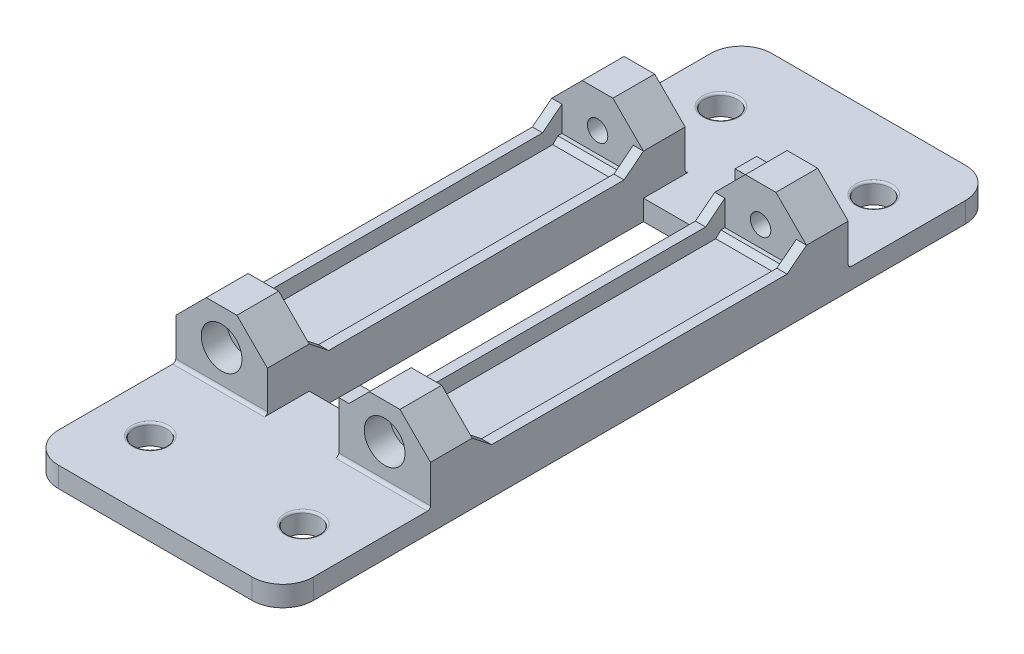
SolidWorks part; units mm, degrees
ref_plane "Front Plane" through (0, 0, 0) normal (0, 0, 1) x (1, 0, 0)
ref_plane "Top Plane" through (0, 0, 0) normal (0, 1, 0) x (1, 0, 0)
ref_plane "Right Plane" through (0, 0, 0) normal (1, 0, 0) x (0, 0, -1)
sketch "Sketch1" plane through (0, 0, 0) normal (0, 1, 0) x (1, 0, 0)
  line L0 (-12.5, -19) -> (-12.5, -12.75)
  line L1 (-12.5, 19) -> (12.5, 19)
  line L2 (-12.5, 19) -> (-12.5, 12.75)
  line L3 (-12.5, -19) -> (12.5, -19)
  line L4 (12.5, 19) -> (12.5, -19)
  line L5 (-14.5, 10.75) -> (-19, 10.75)
  line L7 (-14.5, -10.75) -> (-19, -10.75)
  line L8 (-24, 5.75) -> (-24, -5.75)
  line L9 (-22.342, 7.842) -> (-6.7508, -7.7492) construction
  line L10 (-3, 5) -> (3, 5)
  line L11 (-20.7704, -6.2704) -> (-8.3892, 6.1108) construction
  line L12 (-3, 5) -> (-3, -5)
  line L13 (-3, -5) -> (3, -5)
  line L14 (3, 5) -> (3, -5)
  arc A0 (-24, 5.75) -> (-19, 10.75) centre (-19, 5.75) cw
  arc A1 (-19, -10.75) -> (-24, -5.75) centre (-19, -5.75) cw
  arc A2 (-12.5, 12.75) -> (-14.5, 10.75) centre (-14.5, 12.75) cw
  arc A3 (-12.5, -12.75) -> (-14.5, -10.75) centre (-14.5, -12.75) ccw
  circle A4 centre (-14.5, 0) radius 1.5
  circle A5 centre (0, 8) radius 1
  circle A6 centre (8, 0) radius 1
  circle A7 centre (0, -8) radius 1
  circle A8 centre (-8, 0) radius 1
  circle A9 centre (-20.1569, 5.6569) radius 1
  circle A10 centre (-20.1569, -5.6569) radius 1
  circle A11 centre (-8.8431, -5.6569) radius 1
  circle A12 centre (-8.8431, 5.6569) radius 1
  circle A13 centre (8, 8) radius 1
  circle A14 centre (8, -8) radius 1
  dimension "D8" = 5
  dimension "D9" = 2
  dimension "D10" = 2
  dimension "D11" = 14.5
  dimension "D12" = 8
  dimension "D16" = 8
  dimension "D17" = 8
  dimension "D20" = 8
  dimension "D24" = 3
  dimension "D25" = 3
  dimension "D1" = 12.5
  dimension "D2" = 12.5
  dimension "D3" = 19
  dimension "D4" = 19
  dimension "D5" = 10.75
  dimension "D6" = 10.75
  dimension "D7" = 11.5
  dimension "D13" = 8
  dimension "D14" = 8
  dimension "D15" = 8
  dimension "D18" = 8
  dimension "D19" = 8
  dimension "D21" = 8
  dimension "D22" = 8
  dimension "D23" = 8
  dimension "D26" = 5
  dimension "D27" = 5
extrude "Extrude1" add sketch "Sketch1" along normal blind 3
sketch "Sketch2" plane through (0, 0, 0) normal (0, 1, 0) x (1, 0, 0)
  line L0 (-19.5597, -3.4261) -> (-17.9263, -5.0587)
  line L1 (-19.2603, -2.3108) -> (-16.8108, -4.7603)
  line L2 (-6.3937, 3.2074) -> (-9.7397, 2.3108)
  line L3 (-5.4971, 6.5534) -> (-6.3937, 3.2074)
  line L4 (-20.1569, 5.6569) -> (-8.8431, -5.6569) construction
  line L5 (-7.9466, 9.0029) -> (-5.4971, 6.5534)
  line L6 (-11.2926, 8.1063) -> (-7.9466, 9.0029)
  line L7 (-11.2926, 8.1063) -> (-12.1892, 4.7603)
  line L8 (-7.2104, 4.0234) -> (-9.4413, 3.4263)
  line L9 (-6.6122, 6.254) -> (-7.2104, 4.0234)
  line L10 (-8.2447, 7.8874) -> (-6.6122, 6.254)
  line L11 (-19.5597, -3.4261) -> (-21.7902, -4.0244)
  line L12 (-21.7902, -4.0244) -> (-22.3874, -6.2553)
  line L13 (-22.3874, -6.2553) -> (-20.754, -7.8878)
  line L14 (-20.754, -7.8878) -> (-18.5234, -7.2896)
  line L15 (-18.5234, -7.2896) -> (-17.9263, -5.0587)
  line L16 (-22.6063, -3.2074) -> (-19.2603, -2.3108)
  line L17 (-22.6063, -3.2074) -> (-23.5029, -6.5534)
  line L18 (-23.5029, -6.5534) -> (-21.0534, -9.0029)
  line L19 (-21.0534, -9.0029) -> (-17.7074, -8.1063)
  line L20 (-17.7074, -8.1063) -> (-16.8108, -4.7603)
  line L21 (-10.4756, 7.2902) -> (-8.2447, 7.8874)
  line L22 (-11.0739, 5.0597) -> (-10.4756, 7.2902)
  line L23 (-12.1892, 4.7603) -> (-9.7397, 2.3108)
  line L24 (-11.0739, 5.0597) -> (-9.4413, 3.4263)
  line L25 (-14.5, 13.9789) -> (-14.5, -13.8529) construction
  line L26 (-17.9261, 5.0597) -> (-19.5587, 3.4263)
  line L27 (-16.8108, 4.7603) -> (-19.2603, 2.3108)
  line L28 (-17.9261, 5.0597) -> (-18.5244, 7.2902)
  line L29 (-18.5244, 7.2902) -> (-20.7553, 7.8874)
  line L30 (-20.7553, 7.8874) -> (-22.3878, 6.254)
  line L31 (-22.3878, 6.254) -> (-21.7896, 4.0234)
  line L32 (-21.7896, 4.0234) -> (-19.5587, 3.4263)
  line L33 (-17.7074, 8.1063) -> (-16.8108, 4.7603)
  line L34 (-17.7074, 8.1063) -> (-21.0534, 9.0029)
  line L35 (-21.0534, 9.0029) -> (-23.5029, 6.5534)
  line L36 (-23.5029, 6.5534) -> (-22.6063, 3.2074)
  line L37 (-22.6063, 3.2074) -> (-19.2603, 2.3108)
  line L38 (-5.4971, 0) -> (-25.9289, 0) construction
  line L39 (-11.0739, -5.0597) -> (-9.4413, -3.4263)
  line L40 (-12.1892, -4.7603) -> (-9.7397, -2.3108)
  line L41 (-11.0739, -5.0597) -> (-10.4756, -7.2902)
  line L42 (-10.4756, -7.2902) -> (-8.2447, -7.8874)
  line L43 (-8.2447, -7.8874) -> (-6.6122, -6.254)
  line L44 (-6.6122, -6.254) -> (-7.2104, -4.0234)
  line L45 (-7.2104, -4.0234) -> (-9.4413, -3.4263)
  line L46 (-11.2926, -8.1063) -> (-12.1892, -4.7603)
  line L47 (-11.2926, -8.1063) -> (-7.9466, -9.0029)
  line L48 (-7.9466, -9.0029) -> (-5.4971, -6.5534)
  line L49 (-5.4971, -6.5534) -> (-6.3937, -3.2074)
  line L50 (-6.3937, -3.2074) -> (-9.7397, -2.3108)
  point P57 (-14.5, 0)
extrude "Extrude2" add sketch "Sketch2" along normal blind 4
sketch "Sketch5" plane through (0, 0, 0) normal (0, 1, 0) x (1, 0, 0)
  line L0 (-1.1547, 10) -> (1.1547, 10)
  line L1 (-8, 0) -> (8, 0) construction
  line L2 (4, 15.3149) -> (4, -11.4926) construction
  line L3 (-2.3094, -8) -> (-1.1547, -10)
  line L4 (-1.1547, -6) -> (-2.3094, -8)
  line L5 (1.1547, -6) -> (-1.1547, -6)
  line L6 (2.3094, -8) -> (1.1547, -6)
  line L7 (-3.4641, -8) -> (-1.7321, -11)
  line L8 (-1.7321, -5) -> (-3.4641, -8)
  line L9 (1.7321, -5) -> (-1.7321, -5)
  line L10 (3.4641, -8) -> (1.7321, -5)
  line L11 (-1.7321, 11) -> (1.7321, 11)
  line L12 (1.1547, 10) -> (2.3094, 8)
  line L13 (1.7321, -11) -> (3.4641, -8)
  line L14 (1.1547, -10) -> (2.3094, -8)
  line L15 (-1.7321, -11) -> (1.7321, -11)
  line L16 (1.7321, 11) -> (3.4641, 8)
  line L17 (3.4641, 8) -> (1.7321, 5)
  line L18 (1.7321, 5) -> (-1.7321, 5)
  line L19 (-1.7321, 5) -> (-3.4641, 8)
  line L20 (-3.4641, 8) -> (-1.7321, 11)
  line L21 (2.3094, 8) -> (1.1547, 6)
  line L22 (1.1547, 6) -> (-1.1547, 6)
  line L23 (-1.1547, 6) -> (-2.3094, 8)
  line L24 (-2.3094, 8) -> (-1.1547, 10)
  line L25 (-1.1547, -10) -> (1.1547, -10)
  line L26 (9.1547, -10) -> (6.8453, -10)
  line L27 (10.3094, 8) -> (9.1547, 10)
  line L28 (9.1547, 6) -> (10.3094, 8)
  line L29 (6.8453, 6) -> (9.1547, 6)
  line L30 (5.6906, 8) -> (6.8453, 6)
  line L31 (11.4641, 8) -> (9.7321, 11)
  line L32 (9.7321, 5) -> (11.4641, 8)
  line L33 (6.2679, 5) -> (9.7321, 5)
  line L34 (4.5359, 8) -> (6.2679, 5)
  line L35 (6.2679, 11) -> (4.5359, 8)
  line L36 (9.7321, -11) -> (6.2679, -11)
  line L37 (6.8453, -10) -> (5.6906, -8)
  line L38 (6.2679, -11) -> (4.5359, -8)
  line L39 (6.8453, 10) -> (5.6906, 8)
  line L40 (9.7321, 11) -> (6.2679, 11)
  line L41 (4.5359, -8) -> (6.2679, -5)
  line L42 (6.2679, -5) -> (9.7321, -5)
  line L43 (9.7321, -5) -> (11.4641, -8)
  line L44 (11.4641, -8) -> (9.7321, -11)
  line L45 (5.6906, -8) -> (6.8453, -6)
  line L46 (6.8453, -6) -> (9.1547, -6)
  line L47 (9.1547, -6) -> (10.3094, -8)
  line L48 (10.3094, -8) -> (9.1547, -10)
  line L49 (9.1547, 10) -> (6.8453, 10)
  line L50 (-4.9483, 4) -> (13.5301, 4) construction
  line L51 (9.1547, -2) -> (6.8453, -2)
  line L52 (9.7321, -3) -> (6.2679, -3)
  line L53 (6.8453, -2) -> (5.6906, 0)
  line L54 (6.2679, -3) -> (4.5359, 0)
  line L55 (4.5359, 0) -> (6.2679, 3)
  line L56 (6.2679, 3) -> (9.7321, 3)
  line L57 (9.7321, 3) -> (11.4641, 0)
  line L58 (11.4641, 0) -> (9.7321, -3)
  line L59 (5.6906, 0) -> (6.8453, 2)
  line L60 (6.8453, 2) -> (9.1547, 2)
  line L61 (9.1547, 2) -> (10.3094, 0)
  line L62 (10.3094, 0) -> (9.1547, -2)
  line L63 (0, 0) -> (-15.423, -15.423) construction
  line L64 (-10, -1.1547) -> (-10, 1.1547)
  line L65 (-11, -1.7321) -> (-11, 1.7321)
  line L66 (-10, 1.1547) -> (-8, 2.3094)
  line L67 (-11, 1.7321) -> (-8, 3.4641)
  line L68 (-8, 3.4641) -> (-5, 1.7321)
  line L69 (-5, 1.7321) -> (-5, -1.7321)
  line L70 (-5, -1.7321) -> (-8, -3.4641)
  line L71 (-8, -3.4641) -> (-11, -1.7321)
  line L72 (-8, 2.3094) -> (-6, 1.1547)
  line L73 (-6, 1.1547) -> (-6, -1.1547)
  line L74 (-6, -1.1547) -> (-8, -2.3094)
  line L75 (-8, -2.3094) -> (-10, -1.1547)
  circle A1 centre (0, 8) radius 1 construction
  dimension "D1" = 4
  dimension "D2" = 4
extrude "Extrude3" add sketch "Sketch5" along normal blind 4
sketch "Sketch7" plane through (0, 0, 0) normal (0, 1, 0) x (1, 0, 0)
  line L0 (-12.5, -19) -> (12.5, -19) construction
  line L1 (-12.5, 19) -> (-11.5, 19)
  line L2 (-12.5, 19) -> (-12.5, -19)
  line L3 (-12.5, -19) -> (-11.5, -19)
  line L4 (-11.5, 19) -> (-11.5, -19)
  line L5 (12.5, 19) -> (-12.5, 19) construction
  line L6 (-4.5, 19) -> (-3.5, 19)
  line L7 (-4.5, 19) -> (-4.5, -19)
  line L8 (-4.5, -19) -> (-3.5, -19)
  line L9 (-3.5, 19) -> (-3.5, 6)
  line L10 (3.5, -6) -> (3.5, -19)
  line L11 (3.5, 19) -> (4.5, 19)
  line L12 (3.5, 19) -> (3.5, 6)
  line L13 (3.5, -19) -> (4.5, -19)
  line L14 (4.5, 19) -> (4.5, -19)
  line L15 (12.5, 19) -> (11.5, 19)
  line L16 (12.5, 19) -> (12.5, -19)
  line L17 (12.5, -19) -> (11.5, -19)
  line L18 (11.5, 19) -> (11.5, -19)
  line L19 (3.5, 6) -> (-3.5, 6)
  line L20 (3.5, -6) -> (-3.5, -6)
  line L21 (-3, 5) -> (3, 5)
  line L22 (-3, 5) -> (-3, -5)
  line L23 (-3, -5) -> (3, -5)
  line L24 (3, 5) -> (3, -5)
  line L25 (-3.5, -6) -> (-3.5, -19)
  dimension "D1" = 7
  dimension "D2" = 1
  dimension "D3" = 7
  dimension "D4" = 1
  dimension "D5" = 7
extrude "Extrude4" add sketch "Sketch7" along normal blind 4.5
sketch "Sketch8" plane through (0, 0, 0) normal (0, 1, 0) x (1, 0, 0)
  line L0 (-11.5, 7.3324) -> (-11.5, 19) construction
  line L2 (-11.5, -19) -> (-11.5, -7.3324) construction
  line L3 (-11.5, -9.7489) -> (-11.5, -10.25)
  line L4 (-12, 9.2511) -> (-19, 9.2511)
  line L5 (-11.5, 9.7511) -> (-11.5, 10.2511)
  line L6 (-12, -9.2489) -> (-19, -9.2489)
  line L7 (-11.5, -19) -> (-11.5, 19) construction
  line L8 (-12, -10.75) -> (-19, -10.75)
  line L9 (-24, -5.75) -> (-24, 5.7511)
  line L10 (-19, 10.7511) -> (-12, 10.7511)
  line L12 (-22.5, 5.7511) -> (-22.5, -5.7489)
  arc A0 (-11.5, -9.7489) -> (-12, -9.2489) centre (-12, -9.7489) ccw
  arc A1 (-19, 9.2511) -> (-22.5, 5.7511) centre (-19, 5.7511) ccw
  arc A2 (-19, -9.2489) -> (-22.5, -5.7489) centre (-19, -5.7489) cw
  arc A3 (-24, 5.7511) -> (-19, 10.7511) centre (-19, 5.7511) cw
  arc A4 (-19, -10.75) -> (-24, -5.75) centre (-19, -5.75) cw
  arc A5 (-11.5, -10.25) -> (-12, -10.75) centre (-12, -10.25) cw
  arc A6 (-11.5, 9.7511) -> (-12, 9.2511) centre (-12, 9.7511) cw
  arc A7 (-11.5, 10.2511) -> (-12, 10.7511) centre (-12, 10.2511) ccw
  point P24 (-11.5, -9.2489)
  point P27 (-11.5, -10.75)
  point P30 (-11.5, 9.2511)
  point P33 (-11.5, 10.7511)
  dimension "D1" = 3.5
  dimension "D2" = 3.5
  dimension "D3" = 5
  dimension "D4" = 5
  dimension "D5" = 0.5
extrude "Extrude5" add sketch "Sketch8" along normal blind 6
sketch "Sketch9" plane through (0, 0, 0) normal (0, 1, 0) x (1, 0, 0)
  circle A0 centre (-14.5, 0) radius 5.5
  circle A1 centre (-14.5, 0) radius 1.5
extrude "Extrude10" add sketch "Sketch9" along normal blind 3.5
sketch "Sketch10" plane through (0, 0, 0) normal (0, 1, 0) x (1, 0, 0)
  line L0 (-16.2321, 3) -> (-12.7679, 3)
  line L2 (-16.9537, 4.25) -> (-12.0463, 4.25)
  line L14 (-12.0463, 4.25) -> (-9.5925, 0)
  line L15 (-12.7679, 3) -> (-11.0359, 0)
  line L16 (-11.0359, 0) -> (-12.7679, -3)
  line L17 (-12.7679, -3) -> (-16.2321, -3)
  line L18 (-16.2321, -3) -> (-17.9641, 0)
  line L19 (-17.9641, 0) -> (-16.2321, 3)
  line L20 (-9.5925, 0) -> (-12.0463, -4.25)
  line L21 (-12.0463, -4.25) -> (-16.9537, -4.25)
  line L22 (-16.9537, -4.25) -> (-19.4075, 0)
  line L23 (-19.4075, 0) -> (-16.9537, 4.25)
extrude "Extrude11" add sketch "Sketch10" along normal blind 6
sketch "Sketch12" plane through (0, 0, 0) normal (0, 1, 0) x (1, 0, 0)
  line L0 (-11.5, 4.6098) -> (-11.5, -4.6098)
  line L1 (-11.5, 7.3324) -> (-11.5, 4.0711) construction
  line L2 (-11.5, -4.0711) -> (-11.5, -7.3324) construction
  arc A0 (-11.5, -4.6098) -> (-11.5, 4.6098) centre (-14.5, 0) ccw
extrude "Extrude12" add sketch "Sketch12" along normal blind 4
sketch "Sketch13" plane through (0, 3.5, 0) normal (0, 1, 0) x (-1, 0, 0)
  line L0 (11.0359, 0) -> (12.7679, 3)
  line L1 (12.7679, 3) -> (16.2321, 3)
  line L2 (16.2321, 3) -> (17.9641, 0)
  line L3 (17.9641, 0) -> (16.2321, -3)
  line L4 (16.2321, -3) -> (12.7679, -3)
  line L5 (12.7679, -3) -> (11.0359, 0)
extrude "Cut-Extrude1" cut sketch "Sketch13" along normal blind 4
sketch "Sketch14" plane through (0, 3, 0) normal (0, 1, 0) x (-1, 0, 0)
  line L0 (8, -2.3094) -> (10, -1.1547)
  line L1 (10, -1.1547) -> (10, 1.1547)
  line L2 (10, 1.1547) -> (8, 2.3094)
  line L3 (8, 2.3094) -> (8, -2.3094)
extrude "Cut-Extrude2" cut sketch "Sketch14" along normal blind 4
sketch "Sketch16" plane through (0, 0, 19) normal (0, 0, 1) x (1, 0, 0)
  line L0 (-12.5, 4.5) -> (-12.5, 0) construction
  line L3 (12.5, 0) -> (12.5, 6)
  line L4 (12.5, 6) -> (9.5, 9)
  line L5 (-6.5, 9) -> (-3.5, 6)
  line L7 (-12.5, 0) -> (-12.5, 6)
  line L8 (-12.5, 6) -> (-9.5, 9)
  line L9 (9.5, 9) -> (6.5, 9)
  line L10 (6.5, 9) -> (4.5, 7)
  line L11 (-9.5, 9) -> (-6.5, 9)
  line L12 (-12.5, 0) -> (-3.5, 0)
  line L13 (3.5, 0) -> (12.5, 0)
  line L16 (4.5, 7) -> (0.5, 7)
  line L17 (-2.5, 6) -> (0.5, 7)
  line L18 (-2.5, 6) -> (-2.5, 3)
  line L19 (-2.5, 3) -> (0.5, 2)
  line L20 (0.5, 2) -> (3.5, 2)
  line L21 (3.5, 2) -> (3.5, 0)
  line L23 (-3.5, 0) -> (-3.5, 6)
  circle A0 centre (-8, 5.5) radius 1
  circle A1 centre (8, 5.5) radius 1
  point P0 (-12.5, 2.25)
  dimension "D2" = 16
  dimension "D1" = 4.5
extrude "Extrude13" add sketch "Sketch16" against normal blind 2.6
sketch "Sketch17" plane through (0, 0, 19) normal (0, 0, 1) x (1, 0, 0)
  line L0 (-2.5, 3) -> (0.5, 2)
  line L1 (0.5, 2) -> (4.5, 2)
  line L2 (4.5, 2) -> (4.5, 0)
  line L3 (-12.5, 0) -> (12.5, 0) construction
  line L4 (4.5, 0) -> (-3.5, 0)
  line L5 (-3.5, 3) -> (-2.5, 3)
  line L6 (-3.5, 3) -> (-3.5, 0)
  dimension "D1" = 2
extrude "Cut-Extrude4" cut sketch "Sketch17" against normal blind 3
sketch "Sketch18" plane through (0, 0, 0) normal (0, 1, 0) x (1, 0, 0)
  line L0 (-2.5, -16.4) -> (3.5, -16.4)
  line L1 (3.5, -16.4) -> (3.5, -18)
  line L2 (-2.5, -18) -> (-2.5, -16.4)
  line L3 (-2.5, -16.4) -> (-2.5, -19) construction
  line L4 (-1.5, -18) -> (3.5, -18)
  arc A0 (-1.5, -18) -> (-2.5, -18) centre (-2, -18) ccw
  dimension "D1" = 0.5
extrude "Cut-Extrude5" cut sketch "Sketch18" along normal through all
sketch "Sketch19" plane through (0, 0, 16.4) normal (0, 0, -1) x (-1, 0, 0)
  line L0 (-4.5, 7) -> (-3.5, 6)
  line L1 (-3.5, 7) -> (-3.5, 4.5) construction
  line L2 (-3.5, 6) -> (-3.5, 7)
  line L3 (-3.5, 7) -> (-4.5, 7)
extrude "Cut-Extrude6" cut sketch "Sketch19" against normal blind 2
sketch "Sketch20" plane through (12.5, 0, 0) normal (1, 0, 0) x (0, 0, -1)
  line L0 (-16, 3) -> (-15.5, 3)
  line L1 (-19, 0) -> (19, 0) construction
  line L2 (-16, 3) -> (-16, 3.5)
  line L3 (-16, 3.5) -> (-15.5, 3)
  dimension "D1" = 3
extrude "Extrude14" add sketch "Sketch20" against normal blind 25
sketch "Sketch21" plane through (12.5, 0, 0) normal (1, 0, 0) x (0, 0, -1)
  line L0 (-16.4, 6) -> (-14.5, 4.5)
  line L2 (-16.4, 4.5) -> (19, 4.5) construction
  line L3 (-14.5, 4.5) -> (-16.4, 4.5)
  line L4 (-16.4, 4.5) -> (-16.4, 6)
extrude "Extrude15" add sketch "Sketch21" against normal blind 1
sketch "Sketch22" plane through (4.5, 0, 0) normal (1, 0, 0) x (0, 0, -1)
  line L0 (-16.4, 6) -> (-14.5, 4.5)
  line L1 (-14.5, 4.5) -> (-16.4, 4.5)
  line L2 (-16.4, 4.5) -> (-16.4, 6)
extrude "Extrude17" add sketch "Sketch22" against normal blind 1
sketch "Sketch23" plane through (-3.5, 0, 0) normal (1, 0, 0) x (0, 0, -1)
  line L0 (-16.4, 6) -> (-14.5, 4.5)
  line L1 (-14.5, 4.5) -> (-16.4, 4.5)
  line L2 (-16.4, 4.5) -> (-10.25, 4.5) construction
  line L3 (-16.4, 4.5) -> (-6, 4.5) construction
  line L4 (-16.4, 4.5) -> (-16.4, 6)
extrude "Extrude18" add sketch "Sketch23" against normal blind 1
sketch "Sketch24" plane through (-11.5, 0, 0) normal (1, 0, 0) x (0, 0, -1)
  line L0 (-16.4, 6) -> (-14.5, 4.5)
  line L1 (-14.5, 4.5) -> (-16.4, 4.5)
  line L2 (-16.4, 4.5) -> (-16.4, 6)
extrude "Extrude19" add sketch "Sketch24" against normal blind 1
sketch "Sketch25" plane through (12.5, 0, 0) normal (1, 0, 0) x (0, 0, -1)
  line L0 (-19, 0) -> (-17, 0)
  line L1 (-19, 0) -> (19, 0) construction
  line L2 (-17, 0) -> (-19, 2)
  line L3 (-19, 2) -> (-19, 0)
extrude "Cut-Extrude7" cut sketch "Sketch25" against normal through all
sketch "Sketch26" plane through (0, 0, 19) normal (0, 0, 1) x (1, 0, 0)
  circle A0 centre (-8, 5.5) radius 2
  circle A1 centre (8, 5.5) radius 2
extrude "Cut-Extrude8" cut sketch "Sketch26" against normal blind 1
mirror "Mirror1" about plane through (0, 0, 0) normal (0, 0, 1) of "Cut-Extrude8", "Cut-Extrude7", "Extrude19", "Extrude18", "Extrude17", "Extrude15", "Cut-Extrude6", "Cut-Extrude5", "Extrude13", "Cut-Extrude4", "Extrude14"
sketch "Sketch27" plane through (0, 0, 0) normal (0, -1, 0) x (1, 0, 0)
  circle A0 centre (0, 0) radius 4
extrude "Cut-Extrude9" cut sketch "Sketch27" against normal blind 1.5
sketch "Sketch28" plane through (0, 0, 0) normal (0, -1, 0) x (1, 0, 0)
  circle A0 centre (-14.5, 0) radius 4
extrude "Cut-Extrude10" cut sketch "Sketch28" against normal blind 1
sketch "Sketch29" plane through (-24, 0, 0) normal (-1, 0, 0) x (0, 0, 1)
  line L0 (-2.5005, 6) -> (2.4995, 6)
  line L2 (-0.5005, 4) -> (0.4995, 4)
  arc A0 (-2.5005, 6) -> (-0.5005, 4) centre (-0.5005, 6) ccw
  arc A2 (0.4995, 4) -> (2.4995, 6) centre (0.4995, 6) ccw
  dimension "D2" = 2
extrude "Cut-Extrude11" cut sketch "Sketch29" against normal blind 1.5
fillet "Fillet4" radius 0.25 13 edges at (-11.0231, 6, 2.4779) (-14.5, 6, 4.25) (-18.1806, 6, 2.125) (-18.1806, 6, -2.125) (-14.5, 6, -4.25) (-11.0231, 6, -2.4779) (-10, 6, 0) (-17.0981, 6, 1.5) (-14.5, 6, 3) (-11.9019, 6, 1.5) (-11.9019, 6, -1.5) (-14.5, 6, -3) (-17.0981, 6, -1.5)
sketch "Sketch30" plane through (0, 3.5, 0) normal (0, 1, 0) x (-1, 0, 0)
  line L0 (16.2321, -3) -> (12.7679, -3)
  line L1 (12.7679, -3) -> (11.0359, 0)
  line L2 (4.95, 0) -> (-4.95, 0) construction
  line L3 (11.0359, 0) -> (12.7679, 3) construction
  line L4 (11.0359, 0) -> (12.7679, 3)
  line L5 (16.2321, 3) -> (17.9641, 0)
  line L6 (17.9641, 0) -> (16.2321, 3) construction
  line L7 (17.9641, 0) -> (16.2321, -3)
  line L8 (12.7679, 3) -> (11.0359, 0) construction
  line L9 (12.7679, 3) -> (16.2321, 3)
extrude "Cut-Extrude12" cut sketch "Sketch30" against normal blind 1.5
sketch "Sketch31" plane through (0, 0, 0) normal (0, -1, 0) x (1, 0, 0)
  line L0 (-12.5, -19) -> (-12.5, 19)
  line L1 (-12.5, 19) -> (-28.5028, 19)
  line L2 (-28.5028, 19) -> (-28.5028, -19)
  line L3 (-28.5028, -19) -> (-12.5, -19)
extrude "Cut-Extrude13" cut sketch "Sketch31" against normal through all
sketch "Sketch32" plane through (0, 0, 0) normal (0, 0, -1) x (-1, 0, 0)
  line L12 (0, 12.6124) -> (0, -2.6165) construction
  line L13 (12.8379, 9.6424) -> (4.5, 4.5)
  line L14 (12.8379, 4.5) -> (12.8379, 9.6424)
  line L15 (11.5, 4.5) -> (12.8379, 4.5)
  line L16 (11.5, 3) -> (11.5, 4.5)
  line L17 (4.5, 3) -> (11.5, 3)
  line L18 (4.5, 4.5) -> (4.5, 3)
extrude "Cut-Extrude14" cut sketch "Sketch32" along normal blind 14.5 and the other way blind 14.5
sketch "Sketch33" plane through (0, 0, 0) normal (0, 0, 1) x (1, 0, 0)
  line L1 (-12.5, 0) -> (-3.5, 0) construction
  line L2 (-4.5, 0) -> (-12.5, 0)
  line L3 (-12.5, 0) -> (-12.5, 4.5)
  line L4 (-12.5, 4.5) -> (-11.5, 4.5)
  line L5 (-12.5, 4.5) -> (-11.5, 4.5) construction
  line L6 (-11.5, 6) -> (-11.5, 3) construction
  line L7 (-11.5, 4.5) -> (-11.5, 3)
  line L8 (-11.5, 3) -> (-4.5, 3) construction
  line L9 (-11.0359, 3) -> (-11.5, 3) construction
  line L10 (-11.5, 3) -> (-4.5, 3)
  line L11 (-4.5, 3) -> (-4.5, 3.5) construction
  line L12 (-4.5, 3) -> (-4.5, 0)
extrude "Extrude20" add sketch "Sketch33" along normal blind 15 and the other way blind 15
sketch "Sketch34" plane through (0, 3, 0) normal (0, 1, 0) x (-1, 0, 0)
  line L40 (0, -20.1599) -> (0, 21.0169) construction
  line L41 (6.8453, 6) -> (5.6906, 8)
  line L42 (9.1547, 6) -> (6.8453, 6)
  line L43 (10.3094, 8) -> (9.1547, 6)
  line L44 (9.1547, 10) -> (10.3094, 8)
  line L45 (6.8453, 10) -> (9.1547, 10)
  line L46 (5.6906, 8) -> (6.8453, 10)
  line L47 (6.2679, 5) -> (4.5359, 8)
  line L48 (9.7321, 5) -> (6.2679, 5)
  line L49 (11.4641, 8) -> (9.7321, 5)
  line L50 (9.7321, 11) -> (11.4641, 8)
  line L51 (6.2679, 11) -> (9.7321, 11)
  line L52 (4.5359, 8) -> (6.2679, 11)
  line L53 (6.8453, -2) -> (5.6906, 0)
  line L54 (9.1547, -2) -> (6.8453, -2)
  line L55 (10.3094, 0) -> (9.1547, -2)
  line L56 (9.1547, 2) -> (10.3094, 0)
  line L57 (6.8453, 2) -> (9.1547, 2)
  line L58 (5.6906, 0) -> (6.8453, 2)
  line L59 (6.2679, -3) -> (4.5359, 0)
  line L60 (9.7321, -3) -> (6.2679, -3)
  line L61 (11.4641, 0) -> (9.7321, -3)
  line L62 (9.7321, 3) -> (11.4641, 0)
  line L63 (6.2679, 3) -> (9.7321, 3)
  line L64 (4.5359, 0) -> (6.2679, 3)
  line L65 (6.2679, -11) -> (4.5359, -8)
  line L66 (9.7321, -11) -> (6.2679, -11)
  line L67 (11.4641, -8) -> (9.7321, -11)
  line L68 (9.7321, -5) -> (11.4641, -8)
  line L69 (6.2679, -5) -> (9.7321, -5)
  line L70 (4.5359, -8) -> (6.2679, -5)
  line L71 (6.8453, -10) -> (5.6906, -8)
  line L72 (9.1547, -10) -> (6.8453, -10)
  line L73 (10.3094, -8) -> (9.1547, -10)
  line L74 (9.1547, -6) -> (10.3094, -8)
  line L75 (6.8453, -6) -> (9.1547, -6)
  line L76 (5.6906, -8) -> (6.8453, -6)
extrude "Extrude21" add sketch "Sketch34" along normal blind 1
sketch "Sketch35" plane through (0, 3, 0) normal (0, 1, 0) x (-1, 0, 0)
  line L0 (10.3094, -8) -> (9.1547, -6)
  line L1 (9.1547, -6) -> (6.8453, -6)
  line L2 (5.6906, -8) -> (6.8453, -6)
  line L3 (5.6906, -8) -> (6.8453, -10)
  line L4 (6.8453, -10) -> (9.1547, -10)
  line L5 (9.1547, -10) -> (10.3094, -8)
  line L6 (10.3094, 0) -> (9.1547, 2)
  line L7 (4.95, 0) -> (-4.95, 0) construction
  line L8 (9.1547, 2) -> (6.8453, 2)
  line L9 (6.8453, 2) -> (5.6906, 0)
  line L10 (-2.3094, -8) -> (-1.1547, -6)
  line L11 (5.6906, 0) -> (6.8453, -2) construction
  line L12 (6.8453, -2) -> (9.1547, -2)
  line L13 (9.1547, -2) -> (10.3094, 0)
  line L14 (10.3094, 8) -> (9.1547, 10)
  line L15 (9.1547, 10) -> (6.8453, 10)
  line L16 (6.8453, 10) -> (5.6906, 8)
  line L17 (5.6906, 8) -> (6.8453, 6)
  line L18 (6.8453, 6) -> (9.1547, 6)
  line L19 (9.1547, 6) -> (10.3094, 8)
  line L20 (5.6906, 0) -> (6.8453, -2)
  line L21 (-1.1547, 6) -> (1.1547, 6)
  line L22 (1.1547, 6) -> (2.3094, 8)
  line L23 (2.3094, 8) -> (1.1547, 10)
  line L24 (1.1547, 10) -> (-1.1547, 10)
  line L25 (-1.1547, 10) -> (-2.3094, 8)
  line L26 (-2.3094, 8) -> (-1.1547, 6)
  line L27 (-14.7215, 0) -> (17.2529, 0) construction
  line L28 (-1.1547, -10) -> (-2.3094, -8)
  line L29 (1.1547, -10) -> (-1.1547, -10)
  line L30 (2.3094, -8) -> (1.1547, -10)
  line L31 (1.1547, -6) -> (2.3094, -8)
  line L32 (-1.1547, -6) -> (1.1547, -6)
  line L33 (0, 14.0685) -> (0, -14.4118) construction
  line L34 (-5.6906, 0) -> (-6.8453, -2)
  line L35 (-9.1547, 6) -> (-10.3094, 8)
  line L36 (-6.8453, 6) -> (-9.1547, 6)
  line L37 (-5.6906, 8) -> (-6.8453, 6)
  line L38 (-6.8453, 10) -> (-5.6906, 8)
  line L39 (-9.1547, 10) -> (-6.8453, 10)
  line L40 (-10.3094, 8) -> (-9.1547, 10)
  line L41 (-9.1547, -2) -> (-10.3094, 0)
  line L42 (-6.8453, -2) -> (-9.1547, -2)
  line L43 (-6.8453, 2) -> (-5.6906, 0)
  line L44 (-9.1547, 2) -> (-6.8453, 2)
  line L45 (-10.3094, 0) -> (-9.1547, 2)
  line L46 (-9.1547, -10) -> (-10.3094, -8)
  line L47 (-6.8453, -10) -> (-9.1547, -10)
  line L48 (-5.6906, -8) -> (-6.8453, -10)
  line L49 (-5.6906, -8) -> (-6.8453, -6)
  line L50 (-9.1547, -6) -> (-6.8453, -6)
  line L51 (-10.3094, -8) -> (-9.1547, -6)
extrude "Cut-Extrude15" cut sketch "Sketch35" against normal blind 0.5
sketch "Sketch36" plane through (0, 0, 0) normal (0, -1, 0) x (1, 0, 0)
  line L0 (4.95, 0) -> (-4.95, 0) construction
  circle A0 centre (-8, 8) radius 1
  circle A1 centre (-8, 0) radius 1
  circle A2 centre (-8, -8) radius 1
  circle A3 centre (0, 8) radius 1 construction
  circle A4 centre (0, -8) radius 1 construction
  dimension "D1" = 8
  dimension "D2" = 8
  dimension "D3" = 8
  dimension "D5" = 8
  dimension "D4" = 8
extrude "Cut-Extrude16" cut sketch "Sketch36" against normal blind 10.5
sketch "Sketch37" plane through (0, 0, 0) normal (0, 1, 0) x (1, 0, 0)
  line L0 (4.5, -19) -> (0.5, -19) construction
  line L1 (-3.5, 19) -> (3.5, 19)
  line L2 (-3.5, 19) -> (-3.5, 16.4)
  line L3 (-3.5, 16.4) -> (3.5, 16.4)
  line L4 (3.5, 19) -> (3.5, 16.4)
  line L5 (-3.5, -16.4) -> (3.5, -16.4)
  line L6 (-3.5, -16.4) -> (-3.5, -19)
  line L7 (-3.5, -19) -> (3.5, -19)
  line L8 (3.5, -16.4) -> (3.5, -19)
extrude "Cut-Extrude18" cut sketch "Sketch37" along normal through all
sketch "Sketch38" plane through (0, 0, 0) normal (0, 1, 0) x (1, 0, 0)
  line L1 (12.5, -35) -> (-12.5, -35)
  line L2 (12.5, -35) -> (12.5, 35)
  line L3 (12.5, 35) -> (-12.5, 35)
  line L4 (-12.5, -35) -> (-12.5, 35)
  line L5 (12.5, -35) -> (-12.5, 35) construction
  line L6 (12.5, 35) -> (-12.5, -35) construction
  point P0 (0, 0)
  dimension "D1" = 70
  dimension "D2" = 25
extrude "Boss-Extrude1" add sketch "Sketch38" along normal up to vertex (2 mm away)
fillet "Fillet5" radius 3 4 edges at (12.5, 1, 35) (12.5, 1, -35) (-12.5, 1, 35) (-12.5, 1, -35)
sketch "Sketch40" plane through (0, 4, 0) normal (0, 1, 0) x (1, 0, 0)
  line L0 (4.5, -15.5) -> (4.5, 15.5) construction
  line L1 (11.5, -11) -> (4.5, -11)
  line L2 (11.5, -11) -> (11.5, 11)
  line L3 (11.5, 11) -> (4.5, 11)
  line L4 (4.5, -11) -> (4.5, 11)
  line L5 (11.5, -11) -> (4.5, 11) construction
  line L6 (11.5, 11) -> (4.5, -11) construction
  line L7 (-11.5, -15.5) -> (-11.5, 15.5) construction
  line L8 (-4.5, -11) -> (-11.5, -11)
  line L9 (-4.5, -11) -> (-4.5, 11)
  line L10 (-4.5, 11) -> (-11.5, 11)
  line L11 (-11.5, -11) -> (-11.5, 11)
  line L12 (-4.5, -11) -> (-11.5, 11) construction
  line L13 (-4.5, 11) -> (-11.5, -11) construction
  point P0 (8, 0)
  point P8 (-8, 0)
extrude "Cut-Extrude20" cut sketch "Sketch40" against normal up to vertex (1 mm away)
sketch "Sketch41" plane through (0, 2, 0) normal (0, 1, 0) x (1, 0, 0)
  line L0 (4.5, -15.5) -> (4.5, 15.5) construction
  line L1 (11.5, -10) -> (4.5, -10)
  line L2 (11.5, -10) -> (11.5, 10)
  line L3 (11.5, 10) -> (4.5, 10)
  line L4 (4.5, -10) -> (4.5, 10)
  line L5 (11.5, -10) -> (4.5, 10) construction
  line L6 (11.5, 10) -> (4.5, -10) construction
  line L7 (-11.5, -15.5) -> (-11.5, 15.5) construction
  line L8 (-4.5, -10) -> (-11.5, -10)
  line L9 (-4.5, -10) -> (-4.5, 10)
  line L10 (-4.5, 10) -> (-11.5, 10)
  line L11 (-11.5, -10) -> (-11.5, 10)
  line L12 (-4.5, -10) -> (-11.5, 10) construction
  line L13 (-4.5, 10) -> (-11.5, -10) construction
  point P0 (8, 0)
  point P8 (-8, 0)
extrude "Boss-Extrude2" add sketch "Sketch41" along normal up to vertex
sketch "Sketch44" plane through (0, 4, 0) normal (0, 1, 0) x (1, 0, 0)
  line L1 (-3.5, 6) -> (3.5, 6)
  line L2 (-3.5, 6) -> (-3.5, 16.4)
  line L3 (-3.5, 16.4) -> (3.5, 16.4)
  line L4 (3.5, 6) -> (3.5, 16.4)
  line L5 (-3.5, -6) -> (3.5, -6)
  line L6 (-3.5, -6) -> (-3.5, -16.4)
  line L7 (-3.5, -16.4) -> (3.5, -16.4)
  line L8 (3.5, -6) -> (3.5, -16.4)
extrude "Cut-Extrude22" cut sketch "Sketch44" against normal through all
sketch "Sketch45" plane through (0, 4.5, 0) normal (0, 1, 0) x (1, 0, 0)
  line L1 (3.5, -6) -> (-3.5, -6)
  line L2 (3.5, -6) -> (3.5, 6)
  line L3 (3.5, 6) -> (-3.5, 6)
  line L4 (-3.5, -6) -> (-3.5, 6)
  line L5 (3.5, -6) -> (-3.5, 6) construction
  line L6 (3.5, 6) -> (-3.5, -6) construction
  point P0 (0, 0)
extrude "Cut-Extrude23" cut sketch "Sketch45" against normal through all
sketch "Sketch46" plane through (0, 3, 0) normal (0, 1, 0) x (1, 0, 0)
  line L1 (-11.5, 16.4) -> (-4.5, 16.4)
  line L2 (-11.5, 16.4) -> (-11.5, 16)
  line L3 (-11.5, 16) -> (-4.5, 16)
  line L4 (-4.5, 16.4) -> (-4.5, 16)
  line L5 (4.5, 16.4) -> (11.5, 16.4)
  line L6 (4.5, 16.4) -> (4.5, 16)
  line L7 (4.5, 16) -> (11.5, 16)
  line L8 (11.5, 16.4) -> (11.5, 16)
  line L9 (4.5, -16) -> (11.5, -16)
  line L10 (4.5, -16) -> (4.5, -16.4)
  line L11 (4.5, -16.4) -> (11.5, -16.4)
  line L12 (11.5, -16) -> (11.5, -16.4)
  line L13 (-11.5, -16) -> (-4.5, -16)
  line L14 (-11.5, -16) -> (-11.5, -16.4)
  line L15 (-11.5, -16.4) -> (-4.5, -16.4)
  line L16 (-4.5, -16) -> (-4.5, -16.4)
extrude "Boss-Extrude3" add sketch "Sketch46" along normal up to vertex (0.5 mm away) up to point (-4.5, 3.5, -16)
sketch "Sketch47" plane through (0, 0, 19) normal (0, 0, 1) x (1, 0, 0)
  line L0 (-9.5, 9) -> (-6.5, 9)
  line L1 (-6.5, 9) -> (-3.5, 6)
  line L2 (-3.5, 6) -> (-3.5, 2)
  line L3 (-3.5, 2) -> (-12.5, 2)
  line L4 (-12.5, 2) -> (-12.5, 6)
  line L5 (-12.5, 6) -> (-9.5, 9)
  line L6 (3.5, 7) -> (4.5, 7)
  line L7 (4.5, 7) -> (6.5, 9)
  line L8 (6.5, 9) -> (9.5, 9)
  line L9 (9.5, 9) -> (12.5, 6)
  line L10 (12.5, 6) -> (12.5, 2)
  line L11 (12.5, 2) -> (3.5, 2)
  line L12 (3.5, 2) -> (3.5, 7)
  circle A0 centre (-8, 5.5) radius 2
  circle A1 centre (8, 5.5) radius 2
extrude "Boss-Extrude4" add sketch "Sketch47" along normal blind 1.5
mirror "Mirror2" about plane through (0, 0, 0) normal (0, 0, 1) of "Boss-Extrude4"
fillet "Fillet6" radius 0.3 4 edges at (8, 2, -20.5) (-8, 2, -20.5) (8, 2, 20.5) (-8, 2, 20.5)
sketch "Sketch49" plane through (0, 2, 0) normal (0, 1, 0) x (1, 0, 0)
  line L0 (0, 0) -> (0, 10.4973)
  line L1 (0, 10.4973) -> (0, 0)
  line L2 (0, 0) -> (16.8069, 0)
  line L3 (9.5, 35) -> (-9.5, 35) construction
  line L5 (-12.5, 32) -> (-12.5, 20.8) construction
  circle A0 centre (-7.5, 28) radius 1.6
  circle A1 centre (7.5, 28) radius 1.6
  circle A2 centre (7.5, -28) radius 1.6
  circle A3 centre (-7.5, -28) radius 1.6
  dimension "D1" = 3.2
  dimension "D2" = 7
  dimension "D3" = 5
extrude "Cut-Extrude24" cut sketch "Sketch49" against normal through all contours A1 | A0 | A3 | A2
fillet "Fillet7" radius 0.2 4 edges at (7.5, 2, -26.4) (-7.5, 2, -26.4) (7.5, 2, 29.6) (-7.5, 2, 26.4)
